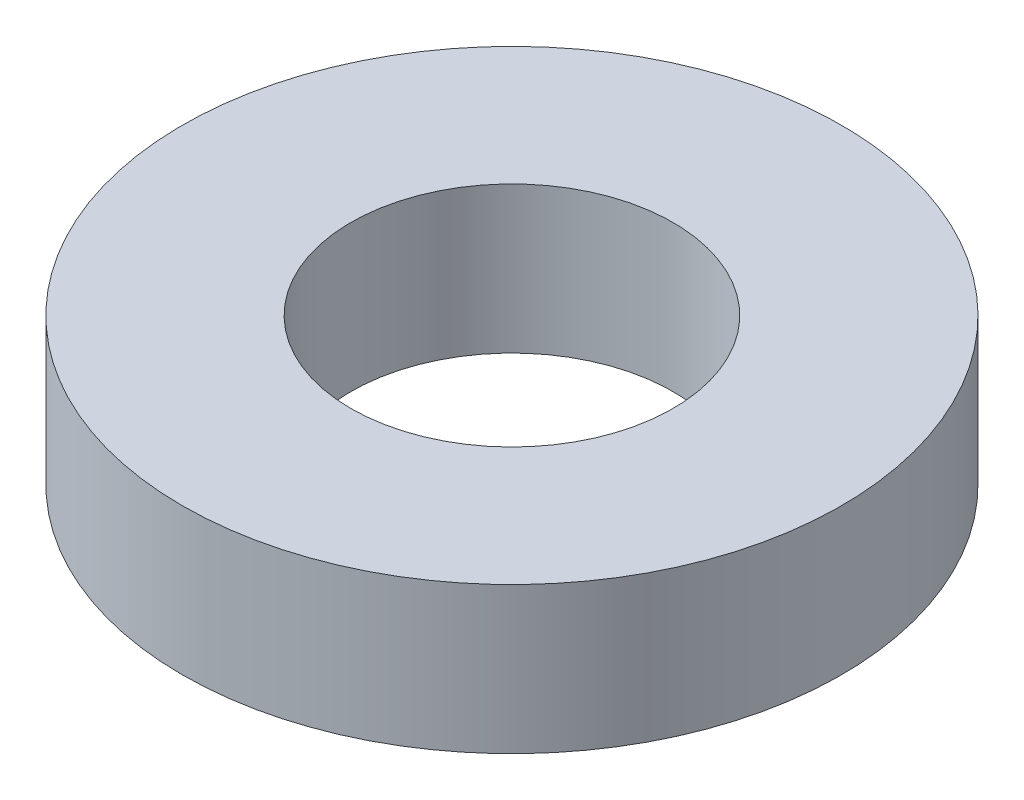
SolidWorks part; units mm, degrees
other "Cable Support Mounting Spacer"
ref_plane "Front Plane" through (0, 0, 0) normal (0, 0, 1) x (1, 0, 0)
ref_plane "Top Plane" through (0, 0, 0) normal (0, 1, 0) x (1, 0, 0)
ref_plane "Right Plane" through (0, 0, 0) normal (1, 0, 0) x (0, 0, -1)
sketch3d "Spacer ring sketch datum points"
  point P0 (-100.2917, -62, -25)
  point P1 (-90.2917, -62, -25)
  point P2 (-100.2917, -62, -35)
ref_plane "Spacer ring sketch plane" through (0, -62, 0) normal (0, 1, 0) x (1, 0, 0)
sketch "Spacer ring sketch" plane through (0, -62, 0) normal (0, 1, 0) x (1, 0, 0)
  circle A0 centre (-100.2917, 25) radius 4.5
  circle A1 centre (-100.2917, 25) radius 2.2
extrude "Spacer ring" add sketch "Spacer ring sketch" along normal blind 2 separate body
